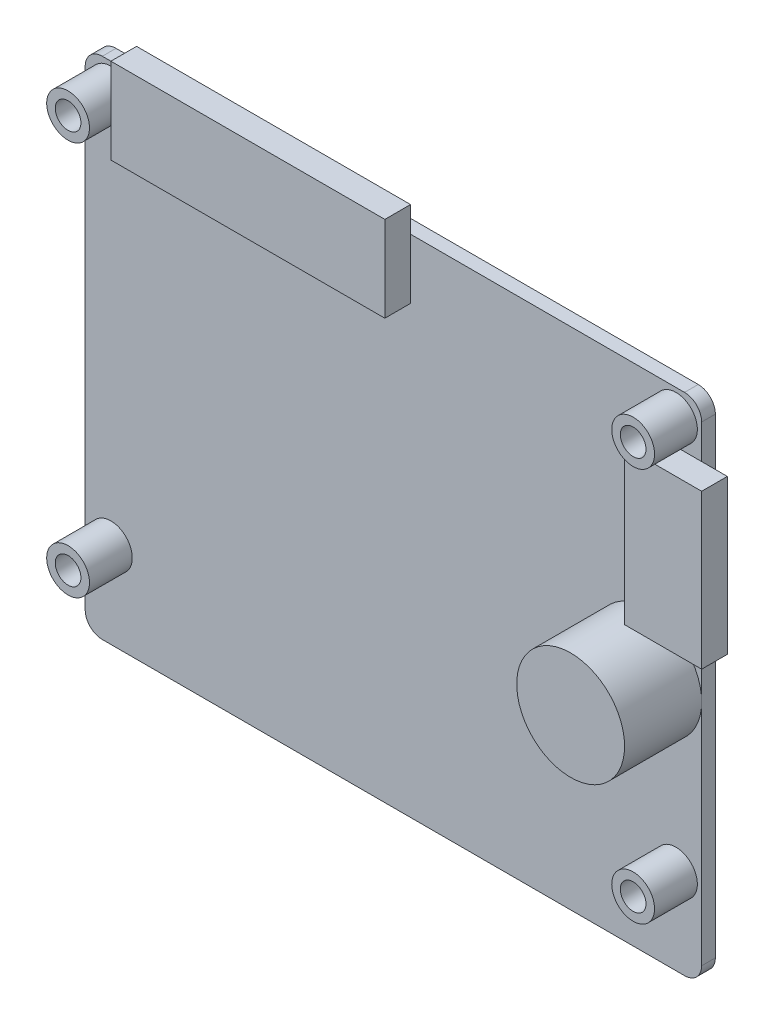
SolidWorks part; units mm, degrees
ref_plane "前视基准面" through (0, 0, 0) normal (0, 0, 1) x (1, 0, 0)
ref_plane "上视基准面" through (0, 0, 0) normal (0, 1, 0) x (1, 0, 0)
ref_plane "右视基准面" through (0, 0, 0) normal (1, 0, 0) x (0, 0, -1)
other "Configuration Table"
sketch "草图1" plane through (0, 0, 0) normal (0, 0, 1) x (1, 0, 0)
  line L0 (-25.0184, 0) -> (20.2354, 0) construction
  line L1 (0, 14.5327) -> (0, -19.4996) construction
  line L3 (-34, -29.5) -> (34, -29.5)
  line L4 (-36, -27.5) -> (-36, 27.5)
  line L5 (-34, 29.5) -> (34, 29.5)
  line L6 (36, -27.5) -> (36, 27.5)
  line L7 (-36, -29.5) -> (36, 29.5) construction
  line L8 (-36, 29.5) -> (36, -29.5) construction
  line L9 (-33, -19.5) -> (33, -19.5) construction
  line L10 (-33, -19.5) -> (-33, 26.5) construction
  line L11 (-33, 26.5) -> (33, 26.5) construction
  line L12 (33, -19.5) -> (33, 26.5) construction
  arc A0 (-36, 27.5) -> (-34, 29.5) centre (-34, 27.5) cw
  arc A1 (-34, -29.5) -> (-36, -27.5) centre (-34, -27.5) cw
  arc A2 (34, -29.5) -> (36, -27.5) centre (34, -27.5) ccw
  arc A3 (34, 29.5) -> (36, 27.5) centre (34, 27.5) cw
  circle A4 centre (-33, 26.5) radius 1.5
  circle A5 centre (33, 26.5) radius 1.5
  circle A6 centre (33, -19.5) radius 1.5
  circle A7 centre (-33, -19.5) radius 1.5
  point P4 (0, 0)
  dimension "D3" = 2
  dimension "D7" = 3
  dimension "D1" = 72
  dimension "D2" = 59
  dimension "D4" = 46
  dimension "D5" = 66
  dimension "D6" = 3
extrude "凸台-拉伸1" add sketch "草图1" along normal blind 1.6
sketch "草图2" plane through (0, 0, 1.6) normal (0, 0, 1) x (1, 0, 0)
  circle A0 centre (33, 26.5) radius 2.5
  circle A1 centre (-33, 26.5) radius 2.5
  circle A2 centre (-33, -19.5) radius 2.5
  circle A3 centre (33, -19.5) radius 2.5
  circle A4 centre (-33, 26.5) radius 1.5 construction
  circle A5 centre (-33, -19.5) radius 1.5 construction
  circle A6 centre (33, -19.5) radius 1.5 construction
  circle A7 centre (33, 26.5) radius 1.5 construction
  circle A8 centre (-33, 26.5) radius 1.5
  circle A9 centre (-33, -19.5) radius 1.5
  circle A10 centre (33, -19.5) radius 1.5
  circle A11 centre (33, 26.5) radius 1.5
  dimension "D1" = 5
extrude "凸台-拉伸2" add sketch "草图2" along normal blind 5
sketch "草图3" plane through (0, 0, 1.6) normal (0, 0, 1) x (1, 0, 0)
  line L0 (36, -27.5) -> (36, 27.5) construction
  line L1 (34, 29.5) -> (-34, 29.5) construction
  circle A0 centre (29.7, -0.8) radius 6.3
  dimension "D1" = 6.3
  dimension "D2" = 30.3
extrude "凸台-拉伸3" add sketch "草图3" along normal blind 9
sketch "草图4" plane through (0, 0, 1.6) normal (0, 0, 1) x (1, 0, 0)
  line L0 (36, 5.5) -> (30, 5.5)
  line L2 (36, 23.5) -> (30, 23.5)
  line L3 (30, 5.5) -> (30, 23.5)
  line L5 (2, 29.5) -> (2, 22.5)
  line L6 (2, 22.5) -> (-30, 22.5)
  line L7 (-30, 29.5) -> (-30, 22.5)
  line L8 (34, 29.5) -> (-34, 29.5) construction
  line L9 (-36, 27.5) -> (-36, -27.5) construction
  line L10 (36, -0.8) -> (36, 27.5) construction
  line L13 (2, 29.5) -> (2, 32.5)
  line L14 (2, 32.5) -> (-30, 32.5)
  line L15 (-30, 29.5) -> (-30, 32.5)
  line L16 (36, 23.5) -> (39, 23.5)
  line L18 (36, 5.5) -> (39, 5.5)
  line L19 (39, 23.5) -> (39, 5.5)
  dimension "D1" = 6
  dimension "D2" = 18
  dimension "D3" = 7
  dimension "D4" = 32
  dimension "D5" = 6
  dimension "D6" = 6
  dimension "D7" = 3
  dimension "D8" = 3
extrude "凸台-拉伸4" add sketch "草图4" along normal blind 3
sketch "草图5" plane through (0, 0, 0) normal (0, 0, -1) x (-1, 0, 0)
  line L0 (-26, 11.5) -> (-17, 11.5)
  line L1 (-26, 11.5) -> (-26, 5)
  line L2 (-26, 5) -> (-17, 5)
  line L3 (-17, 11.5) -> (-17, 5)
  line L4 (-34, 29.5) -> (34, 29.5) construction
  line L5 (-36, -27.5) -> (-36, 27.5) construction
  dimension "D1" = 6.5
  dimension "D2" = 9
  dimension "D3" = 18
  dimension "D4" = 10
extrude "凸台-拉伸5" add sketch "草图5" along normal blind 5
